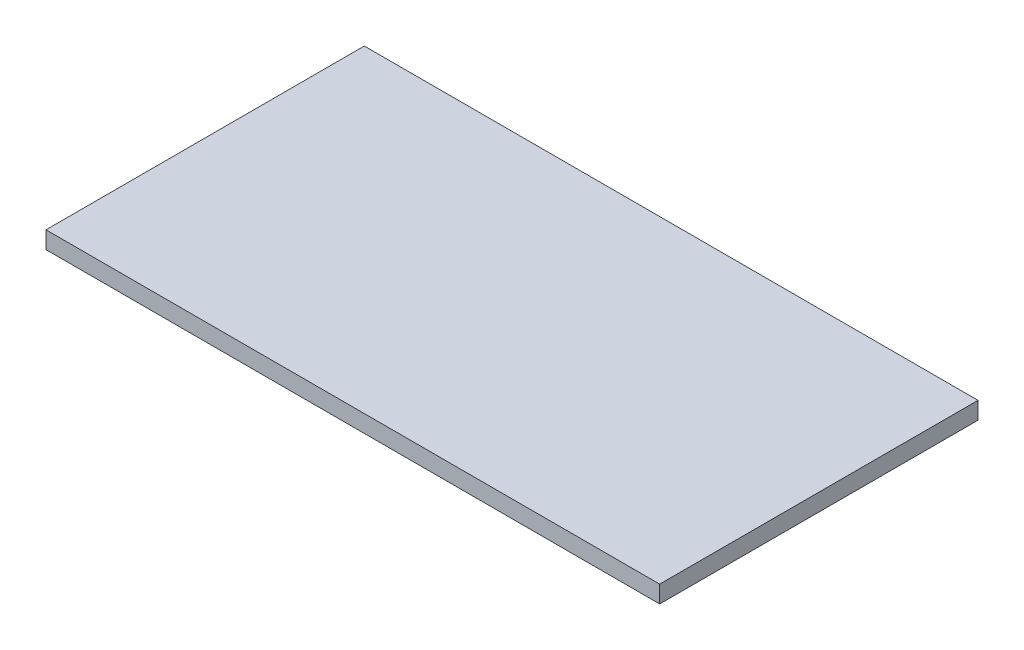
SolidWorks part; units mm, degrees
ref_plane "Front Plane" through (0, 0, 0) normal (0, 0, 1) x (1, 0, 0)
ref_plane "Top Plane" through (0, 0, 0) normal (0, 1, 0) x (1, 0, 0)
ref_plane "Right Plane" through (0, 0, 0) normal (1, 0, 0) x (0, 0, -1)
sketch "Sketch1" plane through (0, 0, 0) normal (0, 1, 0) x (1, 0, 0)
  line L1 (0, 0) -> (214, 0)
  line L2 (0, 0) -> (0, 111)
  line L3 (0, 111) -> (214, 111)
  line L4 (214, 0) -> (214, 111)
  dimension "D1" = 111
  dimension "D2" = 214
extrude "Boss-Extrude1" add sketch "Sketch1" along normal blind 6
